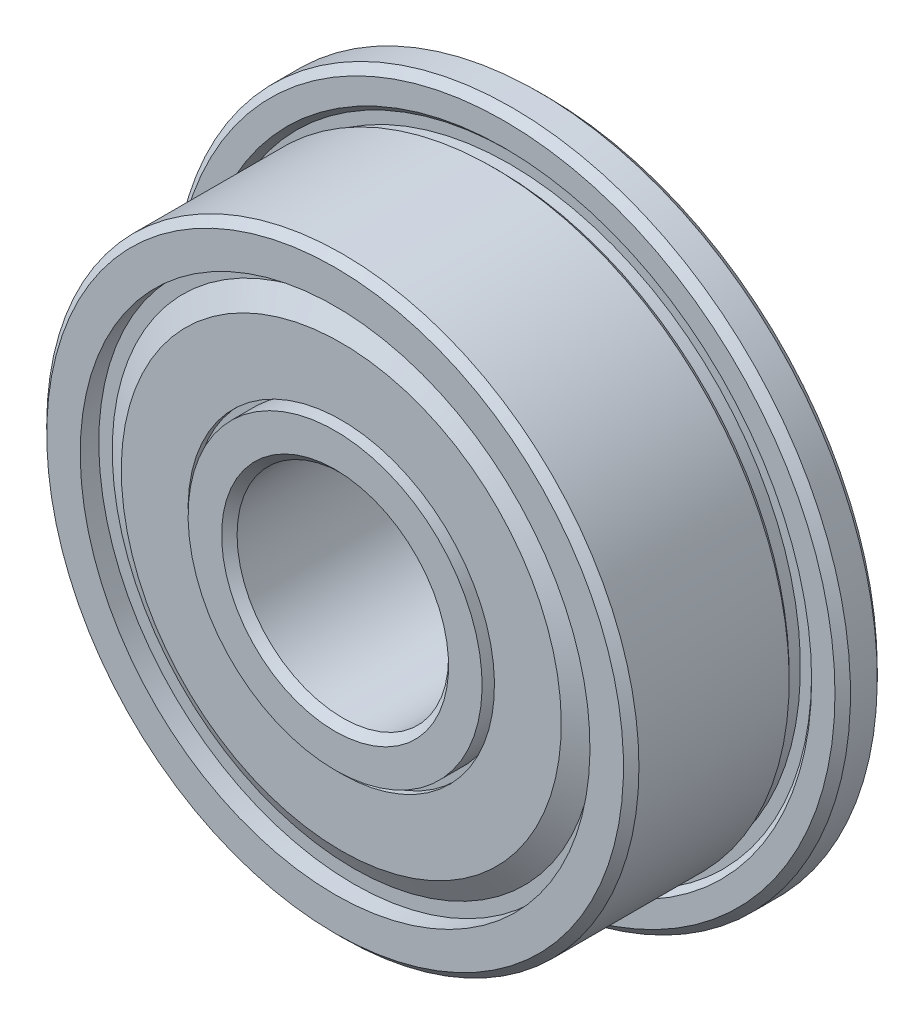
SolidWorks part; units mm, degrees
material "AISI 1045 钢，冷拔"
ref_plane "Front Plane" through (0, 0, 0) normal (0, 0, 1) x (1, 0, 0)
ref_plane "Top Plane" through (0, 0, 0) normal (0, 1, 0) x (1, 0, 0)
ref_plane "Right Plane" through (0, 0, 0) normal (1, 0, 0) x (0, 0, -1)
sketch "Sketch1" plane through (0, 0, 0) normal (1, 0, 0) x (0, 0, -1)
  line L0 (0, 7) -> (0, -7) construction
  line L1 (-2.5, 7) -> (2.5, 7) construction
  line L2 (0, 0) -> (2.5, 0) construction
  line L3 (2.5, 8) -> (2.5, -8) construction
  line L4 (2.5, -8) -> (1.5, -8) construction
  line L5 (2.5, 2.5) -> (0, 2.5) construction
  line L6 (2.5, 2.5) -> (2.5, -2.5) construction
  dimension "OD" = 14
  dimension "Width" = 5
  dimension "Flange Thickness" = 1
  dimension "ID" = 5
  dimension "Flange OD" = 16
sketch "Sketch2" plane through (0, 0, 0) normal (1, 0, 0) x (0, 0, -1)
  line L0 (2.5, 8) -> (1.5, 8)
  line L1 (1.5, 8) -> (1.5, 7.2652)
  line L2 (1.2348, 7) -> (-2.5, 7)
  line L3 (-2.5, 7) -> (-2.5, 5.5375)
  line L4 (-2.5, 5.5375) -> (-0.8928, 5.5375)
  line L5 (2.5, 8) -> (2.5, -8) construction
  line L6 (2.5, 5.5375) -> (2.5, 8)
  line L7 (2.5, 2.5) -> (-2.5, 2.5)
  line L8 (-2.5, 2.5) -> (-2.5, 3.9625)
  line L9 (-2.5, 3.9625) -> (-0.8928, 3.9625)
  line L10 (2.5, 3.9625) -> (2.5, 2.5)
  line L11 (0, 7) -> (0, 2.5) construction
  line L12 (-1.1905, 4.75) -> (1.1905, 4.75) construction
  line L13 (0.8928, 5.5375) -> (2.5, 5.5375)
  line L14 (0.8928, 3.9625) -> (2.5, 3.9625)
  line L15 (1.5, 7.2652) -> (1.6326, 7.1326)
  line L16 (1.6326, 7.1326) -> (1.6326, 6.8674)
  line L17 (1.6326, 6.8674) -> (1.3674, 6.8674)
  line L18 (1.3674, 6.8674) -> (1.2348, 7)
  line L19 (1.5, 7) -> (1.6326, 6.8674) construction
  line L20 (1.6326, 7.1326) -> (1.3674, 6.8674) construction
  line L21 (1.2348, 7) -> (1.5, 7) construction
  line L22 (1.5, 7) -> (1.5, 7.2652) construction
  line L23 (-2.5, 0) -> (2.5, 0) construction
  circle A0 centre (0, 4.75) radius 1.1905 construction
  arc A1 (-0.8928, 5.5375) -> (0.8928, 5.5375) centre (0, 4.75) cw
  arc A2 (-0.8928, 3.9625) -> (0.8928, 3.9625) centre (0, 4.75) ccw
  dimension "Ball Dia." = 2.381
  dimension "D2" = 135
  dimension "D3" = 0.375
  dimension "Race Thikness" = 1.4625
  dimension "D4" = 1.575
revolve "Revolve1" add sketch "Sketch2" angle 360 about L2
fillet "Fillet1" radius 0.1828 3 edges at (0, -8, -2.5) (0, -8, -1.5) (0, -7, 2.5) profile chamfer
sketch "Sketch3" plane through (0, 0, 0) normal (0, 0, 1) x (1, 0, 0)
  line L0 (-2.5, 0) -> (2.5, 0) construction
  line L1 (-7, 0) -> (7, 0) construction
  point P5 (0, 0)
  dimension "ID2" = 5
  dimension "OD2" = 14
fillet "Fillet2" radius 0.1828 2 edges at (0, -2.5, -2.5) (0, -2.5, 2.5) profile chamfer
sketch "Sketch7" plane through (0, 0, 0) normal (0, 0, 1) x (1, 0, 0)
  line L0 (0, 5.9405) -> (0, 3.5595)
  line L1 (0, 8) -> (0, -8) construction
  line L2 (-1.538, 5.9405) -> (0, 0) construction
  line L3 (0, 0) -> (1.538, 5.9405) construction
  line L4 (1.538, 5.9405) -> (-1.538, 5.9405) construction
  circle A0 centre (0, 4.75) radius 1.1905 construction
  circle A1 centre (0, 0) radius 5.9405 construction
  circle A2 centre (0, 0) radius 3.5595 construction
  arc A4 (0, 5.9405) -> (0, 3.5595) centre (0, 4.75) ccw
  dimension "D1" = 29.03
revolve "Revolve3" add sketch "Sketch7" angle 360 about L0
pattern_circular "CirPattern3" count 8 over 360 about axis through (0, 0, 0) along (0, 0, 1) of bodies 107
sketch "Sketch8" plane through (0, 0, 0) normal (1, 0, 0) x (0, 0, -1)
  line L1 (-2.5, 5.5375) -> (-1.915, 5.5375)
  line L2 (-2.5, 5.5375) -> (-2.5, 6.025)
  line L3 (-2.5, 6.025) -> (-1.915, 6.025)
  line L4 (-1.915, 5.5375) -> (-1.915, 6.025)
  line L5 (2.5, 5.5375) -> (1.915, 5.5375)
  line L6 (2.5, 5.5375) -> (2.5, 6.025)
  line L7 (2.5, 6.025) -> (1.915, 6.025)
  line L8 (1.915, 5.5375) -> (1.915, 6.025)
  line L9 (2.5, 3.9625) -> (1.915, 3.9625)
  line L10 (2.5, 3.9625) -> (2.5, 3.475)
  line L11 (2.5, 3.475) -> (1.915, 3.475)
  line L12 (1.915, 3.9625) -> (1.915, 3.475)
  line L13 (-2.5, 3.9625) -> (-1.915, 3.9625)
  line L14 (-2.5, 3.9625) -> (-2.5, 3.475)
  line L15 (-2.5, 3.475) -> (-1.915, 3.475)
  line L16 (-1.915, 3.9625) -> (-1.915, 3.475)
  dimension "D1" = 0.4875
  dimension "D2" = 0.585
revolve "Cut-Revolve1" cut sketch "Sketch8" angle 360 about L2
sketch "Sketch9" plane through (0, 0, 0) normal (1, 0, 0) x (0, 0, -1)
  line L0 (-1.915, 6.025) -> (-1.915, 5.6679)
  line L1 (-1.915, 5.6679) -> (-2.2075, 5.1612)
  line L2 (-2.2075, 5.1612) -> (-2.2075, 3.6212)
  line L3 (2.2075, 3.6213) -> (2.2075, 3.475) construction
  line L4 (1.915, 6.025) -> (1.915, 5.6679)
  line L5 (1.915, 5.6679) -> (2.2075, 5.1612)
  line L6 (2.2075, 5.1612) -> (2.2075, 3.6213)
  line L7 (2.5, 3.475) -> (1.915, 3.475) construction
  line L8 (-2.0613, 6.025) -> (-2.0613, 5.707)
  line L9 (-2.0613, 5.707) -> (-2.3537, 5.2004)
  line L10 (-2.3537, 5.2004) -> (-2.3537, 3.6212)
  line L11 (-1.915, 6.025) -> (-2.0613, 6.025)
  line L12 (-2.2075, 3.6212) -> (-2.3537, 3.6212)
  line L13 (2.0613, 6.025) -> (2.0613, 5.707)
  line L14 (2.0613, 5.707) -> (2.3538, 5.2004)
  line L15 (2.3538, 5.2004) -> (2.3538, 3.6213)
  line L16 (1.915, 6.025) -> (2.0613, 6.025)
  line L17 (2.2075, 3.6213) -> (2.3538, 3.6213)
  line L18 (-1.915, 5.6679) -> (-1.915, 2.5308) construction
  line L19 (1.915, 5.6679) -> (1.915, 6.025) construction
  line L20 (-1.915, 3.475) -> (-2.5, 3.475) construction
  line L22 (-2.2075, 3.6212) -> (-2.2075, 3.475) construction
  dimension "D2" = 150
  dimension "D1" = 150
  dimension "D5" = 0.585
  dimension "D3" = 0.1462
  dimension "D4" = 0.1462
  dimension "D6" = 0.3571
revolve "Revolve4" add sketch "Sketch9" angle 360 about L2
equation "\"D1@Fillet1\"=\"Race Thikness@Sketch2\"/8"
equation "\"ID2@Sketch3\" = \"ID@Sketch1\""
equation "\"OD2@Sketch3\" = \"OD@Sketch1\""
equation "\"D1@Fillet2\"=\"Race Thikness@Sketch2\"/8"
equation "\"D1@CirPattern3\"=360/\"D1@Sketch7\"-4"
equation "\"D1@Sketch8\"=\"Race Thikness@Sketch2\"/3"
equation "\"D2@Sketch8\"=\"Race Thikness@Sketch2\"/2.5"
equation "\"D3@Sketch9\"=\"D5@Sketch9\"/4"
equation "\"D4@Sketch9\"=\"D5@Sketch9\"/4"
equation "\"D1@Sketch9\"=\"D2@Sketch9\""
equation "\"Ball Dia.@Sketch2\" = \"D1@Sketch2\"*.5"
equation "\"D4@Sketch2\"=((\"OD@Sketch1\"-\"ID@Sketch1\")/2)*.35"
